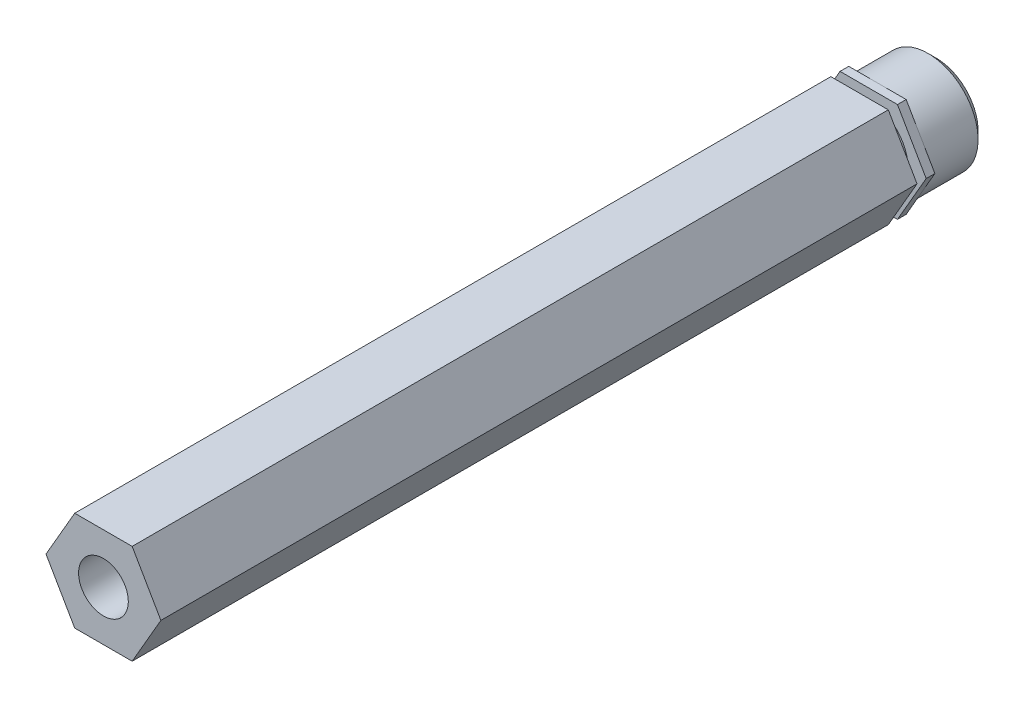
SolidWorks part; units mm, degrees
material "7075-T6 (SN)"
ref_plane "Front Plane" through (0, 0, 0) normal (0, 0, 1) x (1, 0, 0)
ref_plane "Top Plane" through (0, 0, 0) normal (0, 1, 0) x (1, 0, 0)
ref_plane "Right Plane" through (0, 0, 0) normal (1, 0, 0) x (0, 0, -1)
ref_plane "Plane1" through (0, 0, -68.704) normal (0, 0, -1) x (-1, 0, 0)
sketch "Sketch1" plane through (0, 0, -68.704) normal (0, 0, -1) x (-1, 0, 0)
  line L0 (-3.6662, 6.35) -> (-7.3323, 0)
  line L1 (-7.3323, 0) -> (-3.6662, -6.35)
  line L2 (-3.6662, -6.35) -> (3.6662, -6.35)
  line L3 (3.6662, -6.35) -> (7.3323, 0)
  line L4 (7.3323, 0) -> (3.6662, 6.35)
  line L5 (3.6662, 6.35) -> (-3.6662, 6.35)
extrude "Boss-Extrude1" add sketch "Sketch1" against normal blind 1.1116
sketch "Sketch2" plane through (0, 0, -67.5924) normal (0, 0, 1) x (1, 0, 0)
  circle A0 centre (0, 0) radius 5.0292
extrude "Boss-Extrude2" add sketch "Sketch2" along normal blind 1.1684
ref_plane "Plane2" through (0, 0, -66.424) normal (0, 0, -1) x (-1, 0, 0)
sketch "Sketch3" plane through (0, 0, -66.424) normal (0, 0, -1) x (-1, 0, 0)
  line L0 (3.6662, -6.35) -> (7.3323, 0)
  line L1 (7.3323, 0) -> (3.6662, 6.35)
  line L2 (3.6662, 6.35) -> (-3.6662, 6.35)
  line L3 (-3.6662, 6.35) -> (-7.3323, 0)
  line L4 (-7.3323, 0) -> (-3.6662, -6.35)
  line L5 (-3.6662, -6.35) -> (3.6662, -6.35)
extrude "Boss-Extrude3" add sketch "Sketch3" against normal blind 96.52
ref_plane "Plane3" through (0, 0, 0) normal (0, -1, 0) x (1, 0, 0)
sketch "Sketch4" plane through (0, 0, 0) normal (0, -1, 0) x (1, 0, 0)
  line L0 (6.35, -68.704) -> (0, -68.704)
  line L1 (0, -68.704) -> (0, -76.2)
  line L2 (0, -76.2) -> (6.35, -76.2)
  line L3 (6.35, -76.2) -> (6.35, -68.704)
  line L4 (0, -68.704) -> (0, -76.2) construction
revolve "Revolve1" add sketch "Sketch4" angle 360 about L4
chamfer "Chamfer1" distance 1 angle 45 1 edges at (-6.35, 0, -76.2)
sketch "Sketch5" plane through (0, 0, 30.096) normal (0, 0, 1) x (1, 0, 0)
  circle A0 centre (0, 0) radius 3.175
  dimension "D1" = 6.35
extrude "Cut-Extrude1" cut sketch "Sketch5" against normal blind 9.525
